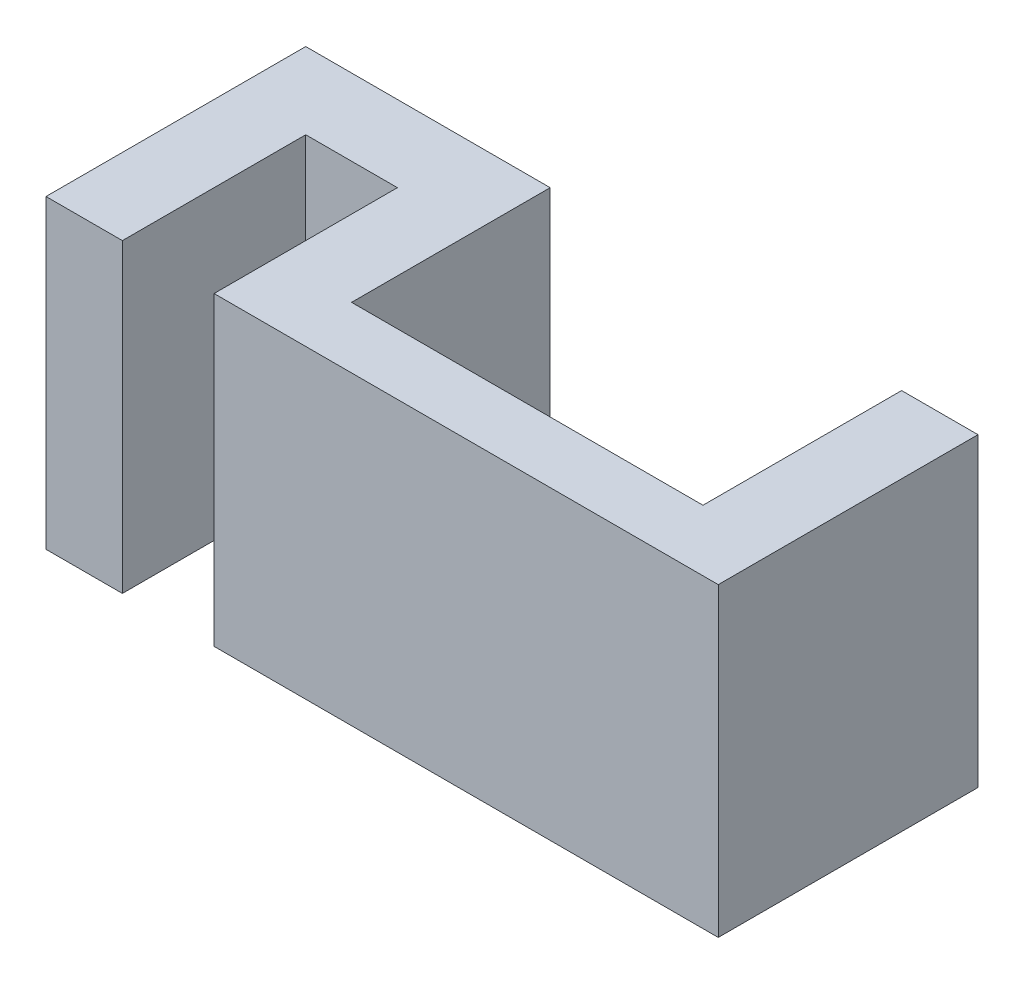
SolidWorks part; units mm, degrees
ref_plane "Front Plane" through (0, 0, 0) normal (0, 0, 1) x (1, 0, 0)
ref_plane "Top Plane" through (0, 0, 0) normal (0, 1, 0) x (1, 0, 0)
ref_plane "Right Plane" through (0, 0, 0) normal (1, 0, 0) x (0, 0, -1)
sketch "Sketch1" plane through (0, 0, 0) normal (0, 1, 0) x (1, 0, 0)
  line L0 (0, 0) -> (-12.7, 0)
  line L1 (-12.7, 0) -> (-12.7, -33.02)
  line L2 (-12.7, -33.02) -> (-71.12, -33.02)
  line L3 (-71.12, -33.02) -> (-71.12, 0)
  line L4 (-71.12, 0) -> (-111.76, 0)
  line L5 (-111.76, 0) -> (-111.76, -43.18)
  line L6 (-111.76, -43.18) -> (-99.06, -43.18)
  line L7 (-99.06, -43.18) -> (-99.06, -12.7)
  line L8 (-99.06, -12.7) -> (-83.82, -12.7)
  line L9 (-83.82, -12.7) -> (-83.82, -43.18)
  line L10 (-83.82, -43.18) -> (0, -43.18)
  line L11 (0, -43.18) -> (0, 0)
  dimension "D1" = 15.24
  dimension "D2" = 12.7
  dimension "D3" = 12.7
  dimension "D4" = 12.7
  dimension "D5" = 10.16
  dimension "D6" = 12.7
  dimension "D7" = 58.42
  dimension "D8" = 33.02
extrude "Boss-Extrude1" add sketch "Sketch1" along normal blind 50.8 contours L7 L8 L9 L10 L11 L0 L1 L2 L3 L4 L5 L6
